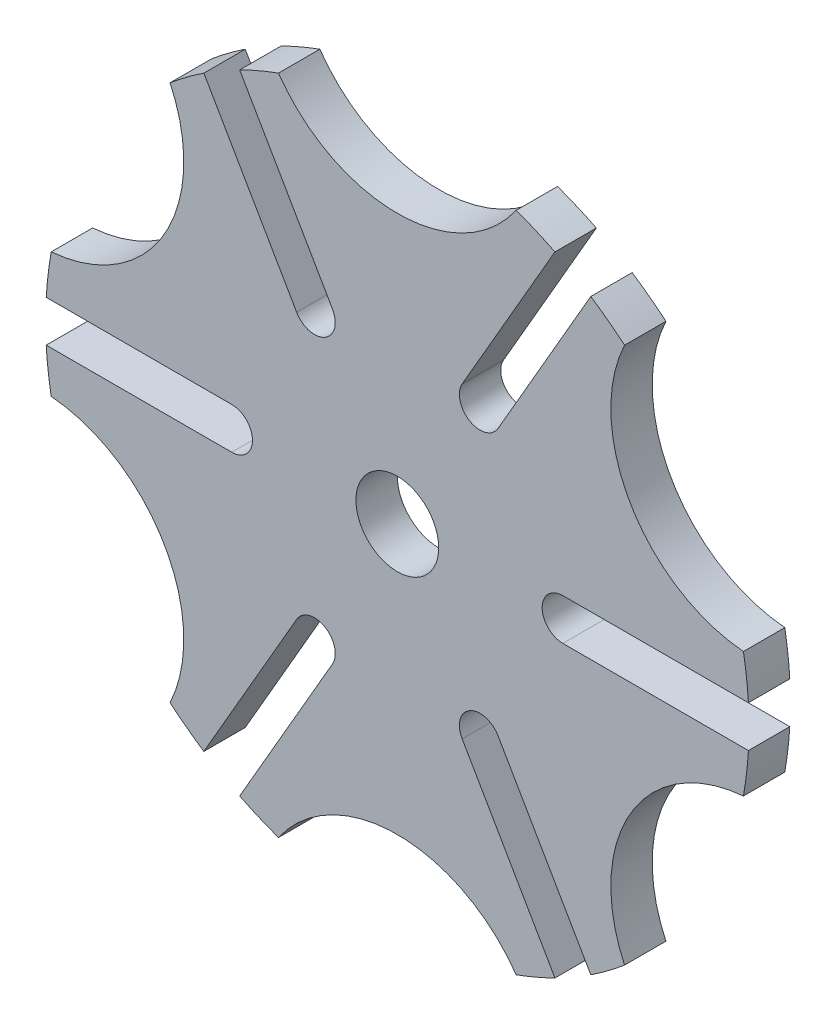
SolidWorks part; units mm, degrees
ref_plane "Alzado" through (0, 0, 0) normal (0, 0, 1) x (1, 0, 0)
ref_plane "Planta" through (0, 0, 0) normal (0, 1, 0) x (1, 0, 0)
ref_plane "Vista lateral" through (0, 0, 0) normal (1, 0, 0) x (0, 0, -1)
sketch "Croquis1" plane through (0, 0, 0) normal (0, 0, 1) x (1, 0, 0)
  circle A0 centre (0, 0) radius 85
  dimension "D1" = 170
extrude "Saliente-Extruir3" add sketch "Croquis1" along normal blind 10
sketch "Croquis3" plane through (0, 0, 10) normal (0, 0, 1) x (1, 0, 0)
  circle A0 centre (0, 0) radius 10
  dimension "D1" = 20
extrude "Cortar-Extruir1" cut sketch "Croquis3" against normal blind 10
sketch "Croquis4" plane through (0, 0, 10) normal (0, 0, 1) x (1, 0, 0)
  line L0 (0, 0) -> (40, 0) construction
  line L1 (40, 5) -> (99.8749, 5)
  line L2 (40, -5) -> (99.8749, -5)
  arc A0 (40, 5) -> (40, -5) centre (40, 0) ccw
  arc A1 (99.8749, -5) -> (99.8749, 5) centre (0, 0) ccw
  dimension "D2" = 10
  dimension "D3" = 200
  dimension "D1" = 40
extrude "Cortar-Extruir2" cut sketch "Croquis4" against normal blind 10
pattern_circular "MatrizC1" count 6 every 60 about axis through (0, 0, 0) along (0, 0, 1) of "Cortar-Extruir2"
sketch "Croquis5" plane through (0, 0, 10) normal (0, 0, 1) x (1, 0, 0)
  line L0 (0, 0) -> (100, 0) construction
  line L1 (0, 0) -> (86.6025, 50) construction
  circle A0 centre (86.6025, 50) radius 35
  dimension "D4" = 70
  dimension "D1" = 100
  dimension "D2" = 30
  dimension "D3" = 100
extrude "Cortar-Extruir3" cut sketch "Croquis5" against normal blind 10
pattern_circular "MatrizC2" count 6 every 60 about axis through (0, 0, 0) along (0, 0, 1) of "Cortar-Extruir3"
